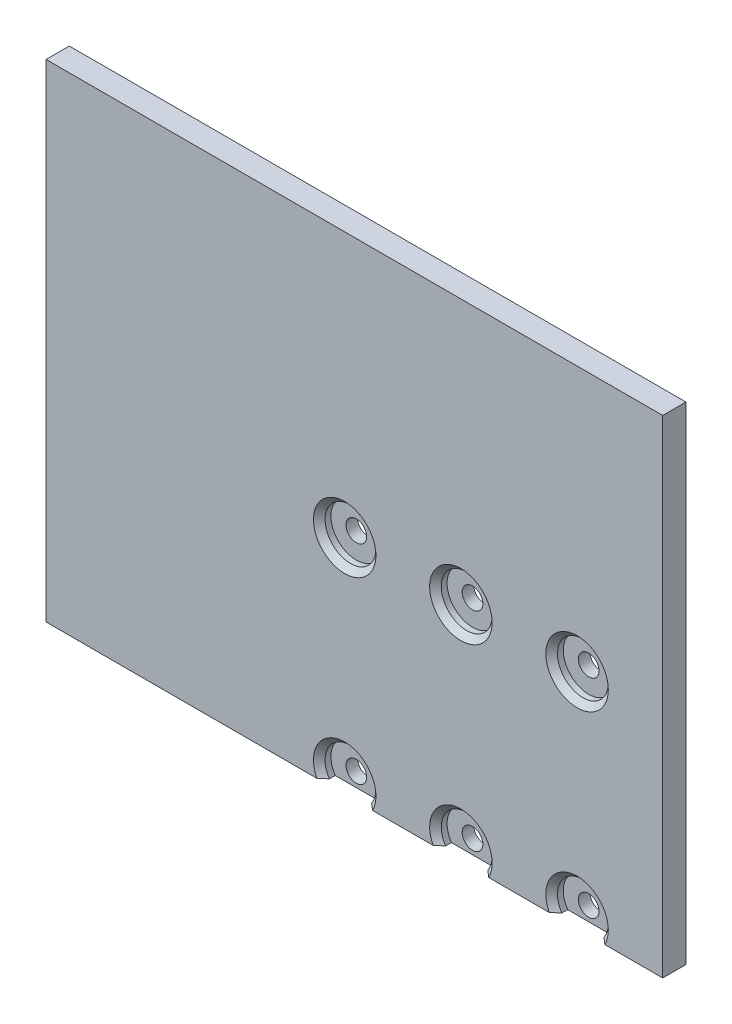
SolidWorks part; units mm, degrees
ref_plane "Front Plane" through (0, 0, 0) normal (0, 0, 1) x (1, 0, 0)
ref_plane "Top Plane" through (0, 0, 0) normal (0, 1, 0) x (1, 0, 0)
ref_plane "Right Plane" through (0, 0, 0) normal (1, 0, 0) x (0, 0, -1)
sketch "Sketch1" plane through (0, 0, 0) normal (0, 0, 1) x (1, 0, 0)
  line L1 (-63.4748, 40.3136) -> (3.9255, 40.3136)
  line L2 (-63.4748, 40.3136) -> (-63.4748, -12.9344)
  line L3 (-63.4748, -12.9344) -> (3.9255, -12.9344)
  line L4 (3.9255, 40.3136) -> (3.9255, -12.9344)
extrude "Boss-Extrude1" add sketch "Sketch1" along normal blind 2.54
hole_wizard "CBORE for #2 Binding Head Machine Screw1" positions "Sketch2" profile "Sketch3" counterbore size "#2" standard "ANSI Inch" end condition through all
sketch "Sketch2" plane through (0, 0, 2.54) normal (0, 0, 1) x (1, 0, 0)
  point P0 (-30.8338, 11.3801)
sketch "Sketch3" plane through (-30.8338, 11.3801, 2.54) normal (1, 0, 0) x (0, -1, 0)
  line L0 (0, 0) -> (0, 2.54)
  line L1 (0, 2.54) -> (1.1303, 2.54)
  line L3 (1.1303, 2.54) -> (1.1303, 1.27)
  line L4 (2.7788, 1.27) -> (1.1303, 1.27)
  line L5 (2.7788, 1.27) -> (2.7788, 0.635)
  line L6 (2.7788, 0.635) -> (3.4138, 0)
  line L7 (3.4138, 0) -> (0, 0)
  line L8 (-2.7788, 0.635) -> (-3.4138, 0) construction
  line L11 (0, -6.35) -> (0, 107.95) construction
  dimension "Thru Hole Dia." = 2.2606
  dimension "Thru Hole Depth" = 2.54
  dimension "C'Bore Dia." = 5.5575
  dimension "C'Bore Depth" = 1.27
  dimension "Near C'Sink Dia." = 6.8275
  dimension "Near C'Sink Angle" = 90
pattern_linear "LPattern1" count 3 spacing 12.7 along (1, 0, 0) of "CBORE for #2 Binding Head Machine Screw1"
mirror "Mirror1" about plane through (0, 0, 0) normal (0, 1, 0) of "CBORE for #2 Binding Head Machine Screw1", "LPattern1"
